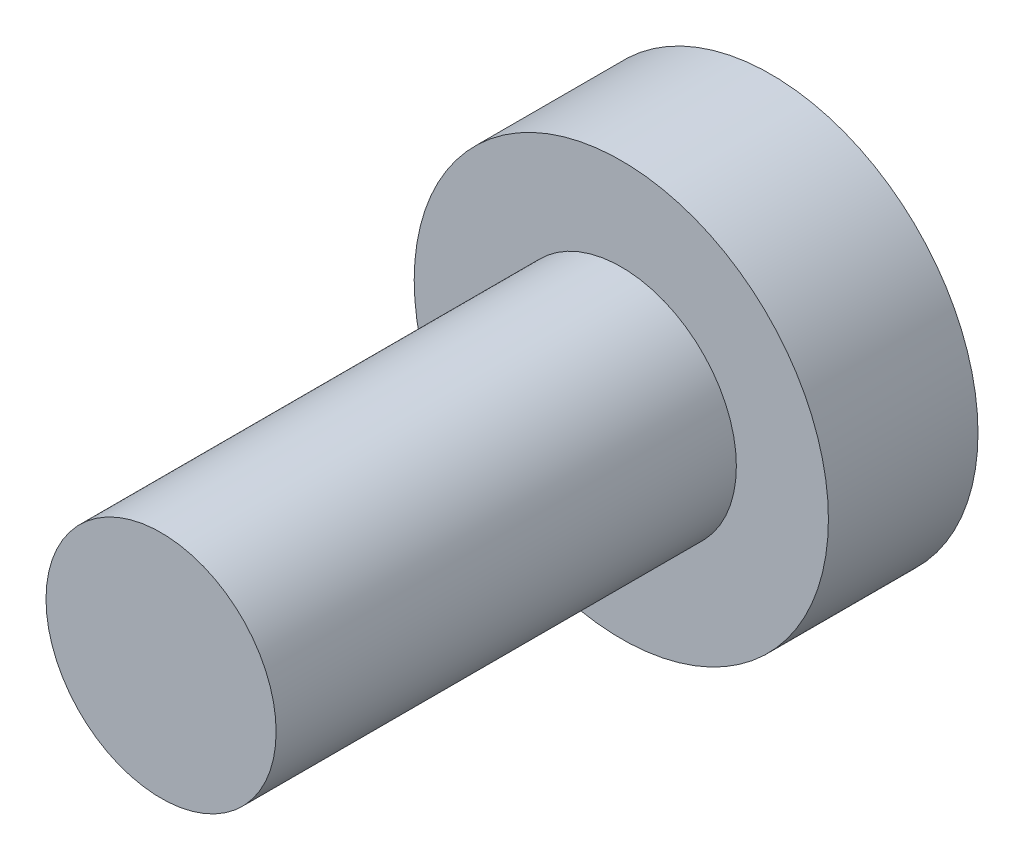
SolidWorks part; units mm, degrees
ref_plane "Спереди" through (0, 0, 0) normal (0, 0, 1) x (1, 0, 0)
ref_plane "Сверху" through (0, 0, 0) normal (0, 1, 0) x (1, 0, 0)
ref_plane "Справа" through (0, 0, 0) normal (1, 0, 0) x (0, 0, -1)
sketch "Эскиз1" plane through (0, 0, 0) normal (0, 0, 1) x (1, 0, 0)
  circle A0 centre (0, 0) radius 1.8
  dimension "D1" = 3.6
extrude "Бобышка-Вытянуть1" add sketch "Эскиз1" along normal blind 1.3
sketch "Эскиз2" plane through (0, 0, 1.3) normal (0, 0, 1) x (1, 0, 0)
  circle A0 centre (0, 0) radius 1
extrude "Бобышка-Вытянуть2" add sketch "Эскиз2" along normal blind 4
